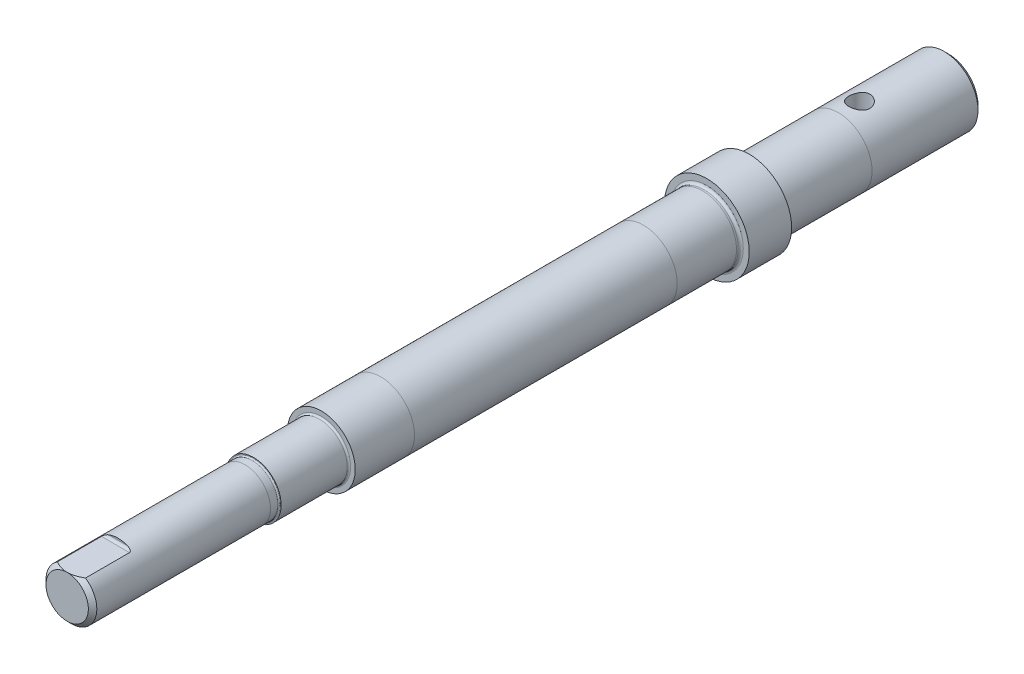
SolidWorks part; units mm, degrees
material "Aleación 1060"
ref_plane "Alzado" through (0, 0, 0) normal (0, 0, 1) x (1, 0, 0)
ref_plane "Planta" through (0, 0, 0) normal (0, 1, 0) x (1, 0, 0)
ref_plane "Vista lateral" through (0, 0, 0) normal (1, 0, 0) x (0, 0, -1)
sketch "Croquis1" plane through (0, 0, 0) normal (0, 0, 1) x (1, 0, 0)
  circle A0 centre (0, 0) radius 4
  dimension "D1" = 8
extrude "Saliente-Extruir1" add sketch "Croquis1" along normal mid plane 104
ref_plane "Plano2" through (3, 0, 0) normal (1, 0, 0) x (0, 0, -1)
ref_plane "Plano3" through (0, 0, -28.5) normal (0, 0, 1) x (1, 0, 0)
sketch "Croquis2" plane through (0, 0, -28.5) normal (0, 0, 1) x (1, 0, 0)
  circle A0 centre (0, 0) radius 5
  dimension "D1" = 10
extrude "Saliente-Extruir2" add sketch "Croquis2" along normal blind 5
sketch "Croquis3" plane through (0, 0, 52) normal (0, 0, 1) x (1, 0, 0)
  circle A0 centre (0, 0) radius 3
  circle A1 centre (0, 0) radius 4 construction
  circle A2 centre (0, 0) radius 4
  dimension "D1" = 6
extrude "Cortar-Extruir1" cut sketch "Croquis3" against normal blind 22
other "M8 Roscas Standard Taladro1" parameters "D1"=8, "D2"=10, "D3"=8, "D4"=8
sketch "Croquis4" [suppressed] plane through (0, 0, 30) normal (1, 0, 0) x (0, 1, 0)
  line L5 (0, -14.3089) -> (0, 0) construction
  line L6 (3.3095, 0) -> (4, -0.6905)
  line L9 (4, -0.6905) -> (4, -8) construction
  line L10 (3.3095, 0) -> (4, 0)
  line L13 (4, -0.6905) -> (4, 0)
  dimension "Minor Diameter" = 6.619
  dimension "Major Diameter" = 8
  dimension "Thread Length" = 8
  dimension "Chamfer Angle" = 45
cosmetic thread "Rosca del espárrago1" [suppressed]
ref_plane "Plano4" through (0, 4, 0) normal (0, 1, 0) x (1, 0, 0)
sketch "Croquis5" plane through (0, 4, 0) normal (0, 1, 0) x (1, 0, 0)
  line L0 (4, 52) -> (-4, 52) construction
  circle A0 centre (0, 41.5) radius 1.25
  dimension "D1" = 2.5
  dimension "D2" = 10.5
extrude "Cortar-Extruir2" cut sketch "Croquis5" against normal through all
chamfer "Chaflán1" distance 0.5 angle 45 2 edges at (4, 0, -52) (3, 0, 52)
ref_plane "Plano5" through (0, 2.5, 0) normal (0, 1, 0) x (1, 0, 0)
sketch "Croquis6" plane through (0, 2.5, 0) normal (0, 1, 0) x (1, 0, 0)
  line L1 (3, -52) -> (-3, -52)
  line L2 (3, -52) -> (3, -46)
  line L3 (3, -46) -> (-3, -46)
  line L4 (-3, -52) -> (-3, -46)
  line L6 (-2.5, -52) -> (2.5, -52) construction
  point P4 (0, -52)
  dimension "D1" = 6
  dimension "D2" = 6
extrude "Cortar-Extruir3" cut sketch "Croquis6" along normal through all
sketch "Croquis7" plane through (0, 0, 30) normal (0, 0, 1) x (1, 0, 0)
  circle A0 centre (0, 0) radius 3.25
  circle A1 centre (0, 0) radius 4 construction
  circle A2 centre (0, 0) radius 4
  dimension "D1" = 6.5
extrude "Cortar-Extruir4" cut sketch "Croquis7" against normal blind 8
fillet "Redondeo2" radius 0.15 1 edges at (3, 0, 30)
fillet "Redondeo3" radius 0.2 1 edges at (3.25, 0, 22)
fillet "Redondeo1" radius 0.3 1 edges at (4, 0, -23.5)
fillet "Redondeo4" radius 0.3 1 edges at (4, 0, -28.5)
fillet "Redondeo5" radius 0.3 1 edges at (0, 2.5, 46)
ref_plane "Plano7" through (0, 0, -16) normal (0, 0, 1) x (1, 0, 0)
ref_plane "Plano10" through (0, 0, -23) normal (0, 0, 1) x (1, 0, 0)
split line "Línea de partición5"
ref_plane "Plano8" through (0, 0, 22) normal (0, 0, 1) x (1, 0, 0)
ref_plane "Plano9" through (0, 0, 15) normal (0, 0, 1) x (1, 0, 0)
split line "Línea de partición6"
ref_plane "Plano11" through (0, 0, -39) normal (0, 0, -1) x (-1, 0, 0)
split line "Línea de partición7"
ref_plane "Plano6" through (0, 0, 31) normal (0, 0, 1) x (1, 0, 0)
ref_plane "Plano12" through (0, 0, 51.5) normal (0, 0, 1) x (1, 0, 0)
split line "Línea de partición8"
